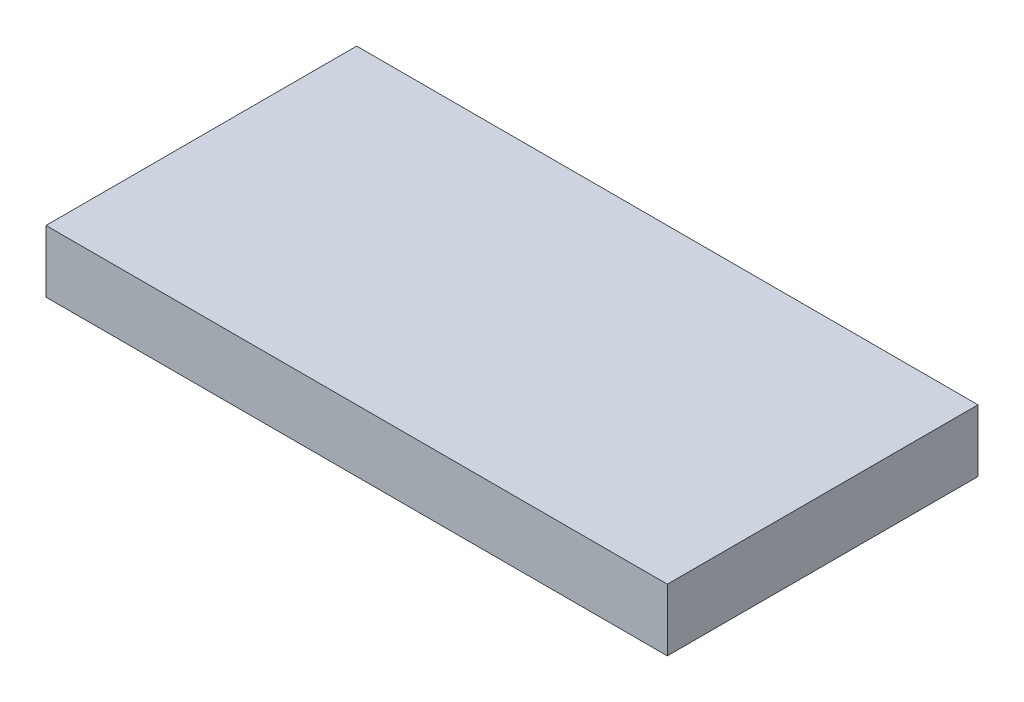
SolidWorks part; units mm, degrees
material "S-Glass Fiber"
ref_plane "Front" through (0, 0, 0) normal (0, 0, 1) x (1, 0, 0)
ref_plane "Top" through (0, 0, 0) normal (0, 1, 0) x (1, 0, 0)
ref_plane "Right" through (0, 0, 0) normal (1, 0, 0) x (0, 0, -1)
sketch "Sketch1" plane through (0, 0, 0) normal (0, 1, 0) x (1, 0, 0)
  line L1 (-15, -7.5) -> (15, -7.5)
  line L2 (-15, -7.5) -> (-15, 7.5)
  line L3 (-15, 7.5) -> (15, 7.5)
  line L4 (15, -7.5) -> (15, 7.5)
  line L5 (-15, -7.5) -> (15, 7.5) construction
  line L6 (-15, 7.5) -> (15, -7.5) construction
  point P0 (0, 0)
  dimension "D1" = 15
  dimension "D2" = 30
extrude "Boss-Extrude1" add sketch "Sketch1" along normal blind 3
